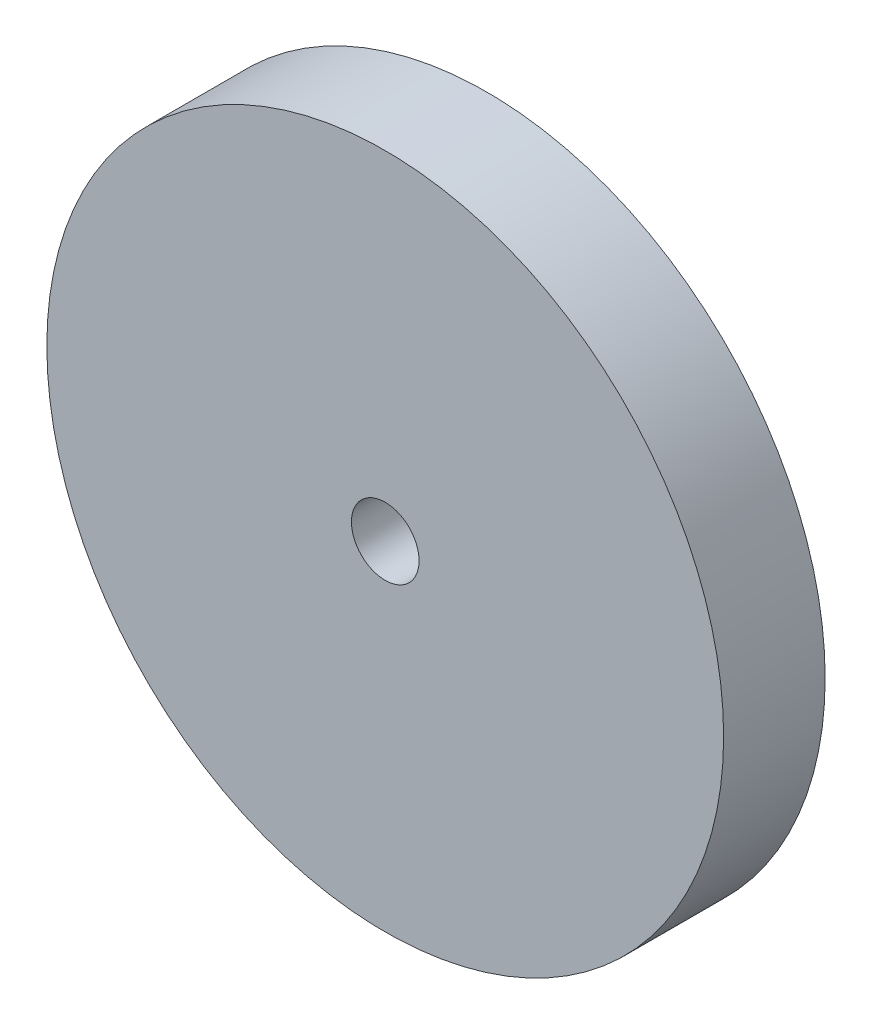
SolidWorks part; units mm, degrees
ref_plane "Front Plane" through (0, 0, 0) normal (0, 0, 1) x (1, 0, 0)
ref_plane "Top Plane" through (0, 0, 0) normal (0, 1, 0) x (1, 0, 0)
ref_plane "Right Plane" through (0, 0, 0) normal (1, 0, 0) x (0, 0, -1)
sketch "Sketch1" plane through (0, 0, 0) normal (0, 0, 1) x (1, 0, 0)
  circle A0 centre (0, 0) radius 100
  circle A1 centre (0, 0) radius 10
  dimension "D1" = 200
  dimension "D2" = 20
extrude "Boss-Extrude1" add sketch "Sketch1" along normal blind 30
